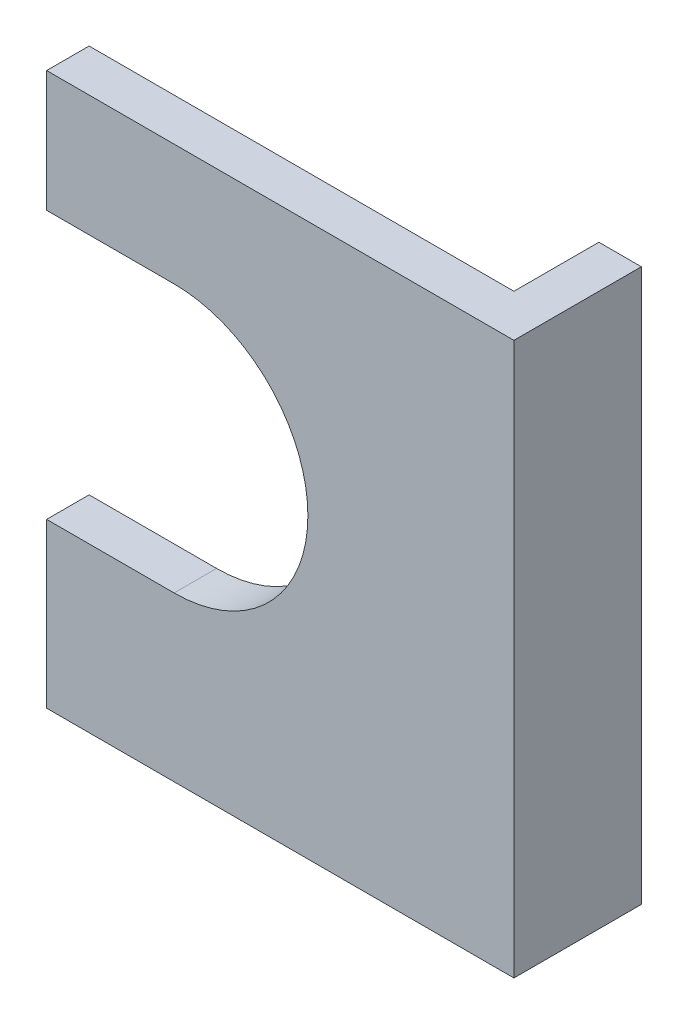
SolidWorks part; units mm, degrees
ref_plane "Front Plane" through (0, 0, 0) normal (0, 0, 1) x (1, 0, 0)
ref_plane "Top Plane" through (0, 0, 0) normal (0, 1, 0) x (1, 0, 0)
ref_plane "Right Plane" through (0, 0, 0) normal (1, 0, 0) x (0, 0, -1)
sketch "Sketch1" plane through (0, 0, 0) normal (1, 0, 0) x (0, 0, -1)
  line L0 (0, -10) -> (0, 90)
  line L1 (0, 90) -> (10, 90)
  line L2 (10, 90) -> (10, 0)
  line L3 (10, 0) -> (25, 0)
  line L4 (25, 0) -> (25, -10)
  line L5 (25, -10) -> (0, -10)
  dimension "D1" = 10
  dimension "D2" = 10
  dimension "D3" = 100
  dimension "D4" = 15
extrude "Boss-Extrude1" add sketch "Sketch1" along normal blind 60
sketch "Sketch4" plane through (60, 0, 0) normal (1, 0, 0) x (0, 0, -1)
  line L3 (0, 0) -> (0, 90)
  line L4 (0, 90) -> (10, 90)
  line L5 (10, 90) -> (10, 0)
  line L6 (10, 0) -> (0, 0)
extrude "Boss-Extrude2" add sketch "Sketch4" along normal blind 45
sketch "Sketch6" plane through (60, 0, 0) normal (1, 0, 0) x (0, 0, -1)
  line L0 (25, 0) -> (10, 0) construction
  line L1 (0, -10) -> (25, -10)
  line L2 (0, -10) -> (0, 0)
  line L3 (0, 0) -> (25, 0)
  line L4 (25, -10) -> (25, 0)
extrude "Boss-Extrude3" add sketch "Sketch6" along normal blind 45
sketch "Sketch8" plane through (0, 0, 0) normal (0, 1, 0) x (1, 0, 0)
  line L0 (105, 10) -> (0, 10) construction
  line L1 (105, 25) -> (95, 25)
  line L2 (105, 25) -> (105, 10)
  line L3 (105, 10) -> (95, 10)
  line L4 (95, 25) -> (95, 10)
  dimension "D1" = 10
extrude "Boss-Extrude4" add sketch "Sketch8" along normal blind 90
sketch "Sketch10" plane through (0, 0, 0) normal (-1, 0, 0) x (0, 0, 1)
  line L6 (0, -10) -> (0, 90)
  line L7 (0, 90) -> (-10, 90)
  line L8 (-10, 90) -> (-10, 0)
  line L9 (-10, 0) -> (-25, 0)
  line L10 (-25, 0) -> (-25, -10)
  line L11 (-25, -10) -> (0, -10)
  line L12 (0, -10) -> (0, 90)
  line L13 (0, 90) -> (-10, 90)
  line L14 (-10, 90) -> (-10, 0)
  line L15 (-10, 0) -> (-25, 0)
  line L16 (-25, 0) -> (-25, -10)
  line L17 (-25, -10) -> (0, -10)
  dimension "D1" = 0
extrude "Boss-Extrude5" add sketch "Sketch10" along normal blind 30
sketch "Sketch11" plane through (0, 90, 0) normal (0, 1, 0) x (1, 0, 0)
  line L12 (-30, 10) -> (-30, 0)
  line L13 (-30, 0) -> (105, 0)
  line L14 (105, 0) -> (105, 25)
  line L15 (105, 25) -> (95, 25)
  line L16 (95, 25) -> (95, 10)
  line L17 (95, 10) -> (-30, 10)
  line L18 (-30, 10) -> (-30, 0)
  line L19 (-30, 0) -> (105, 0)
  line L20 (105, 0) -> (105, 25)
  line L21 (105, 25) -> (95, 25)
  line L22 (95, 25) -> (95, 10)
  line L23 (95, 10) -> (-30, 10)
  dimension "D1" = 0
extrude "Boss-Extrude6" add sketch "Sketch11" along normal blind 30
sketch "Sketch12" plane through (0, 0, -10) normal (0, 0, -1) x (-1, 0, 0)
  line L0 (-95, 120) -> (-95, 0) construction
  line L1 (-67.1329, 60) -> (73.6064, 60) construction
  line L3 (-95, 0) -> (30, 0) construction
  line L4 (-25, 91.5) -> (30, 91.5)
  line L5 (30, 120) -> (30, 0) construction
  line L6 (-25, 28.5) -> (30, 28.5)
  line L7 (30, 91.5) -> (30, 28.5)
  arc A0 (-25, 91.5) -> (-25, 28.5) centre (-25, 60) ccw
  dimension "D1" = 63
  dimension "D2" = 70
  dimension "D3" = 60
extrude "Cut-Extrude1" cut sketch "Sketch12" against normal blind 30
sketch "Sketch13" plane through (-30, 0, 0) normal (-1, 0, 0) x (0, 0, 1)
  line L6 (0, 28.5) -> (-10, 28.5)
  line L7 (-10, 28.5) -> (-10, 0)
  line L8 (-10, 0) -> (-25, 0)
  line L9 (-25, 0) -> (-25, -10)
  line L10 (-25, -10) -> (0, -10)
  line L11 (0, -10) -> (0, 28.5)
  line L12 (0, 28.5) -> (-10, 28.5)
  line L13 (-10, 28.5) -> (-10, 0)
  line L14 (-10, 0) -> (-25, 0)
  line L15 (-25, 0) -> (-25, -10)
  line L16 (-25, -10) -> (0, -10)
  line L17 (0, -10) -> (0, 28.5)
  dimension "D1" = 0
extrude "Cut-Extrude2" cut sketch "Sketch13" against normal blind 25
sketch "Sketch14" plane through (-30, 0, 0) normal (-1, 0, 0) x (0, 0, 1)
  line L4 (-10, 91.5) -> (0, 91.5)
  line L5 (0, 91.5) -> (0, 120)
  line L6 (0, 120) -> (-10, 120)
  line L7 (-10, 120) -> (-10, 91.5)
  line L8 (-10, 91.5) -> (0, 91.5)
  line L9 (0, 91.5) -> (0, 120)
  line L10 (0, 120) -> (-10, 120)
  line L11 (-10, 120) -> (-10, 91.5)
  dimension "D1" = 0
extrude "Cut-Extrude3" cut sketch "Sketch14" against normal blind 25
sketch "Sketch15" plane through (0, 0, -25) normal (0, 0, -1) x (-1, 0, 0)
  line L6 (5, -10) -> (5, 0)
  line L7 (5, 0) -> (-95, 0)
  line L8 (-95, 0) -> (-95, 120)
  line L9 (-95, 120) -> (-105, 120)
  line L10 (-105, 120) -> (-105, -10)
  line L11 (-105, -10) -> (5, -10)
  line L12 (5, -10) -> (5, 0)
  line L13 (5, 0) -> (-95, 0)
  line L14 (-95, 0) -> (-95, 120)
  line L15 (-95, 120) -> (-105, 120)
  line L16 (-105, 120) -> (-105, -10)
  line L17 (-105, -10) -> (5, -10)
  dimension "D1" = 0
extrude "Boss-Extrude7" add sketch "Sketch15" along normal blind 5
